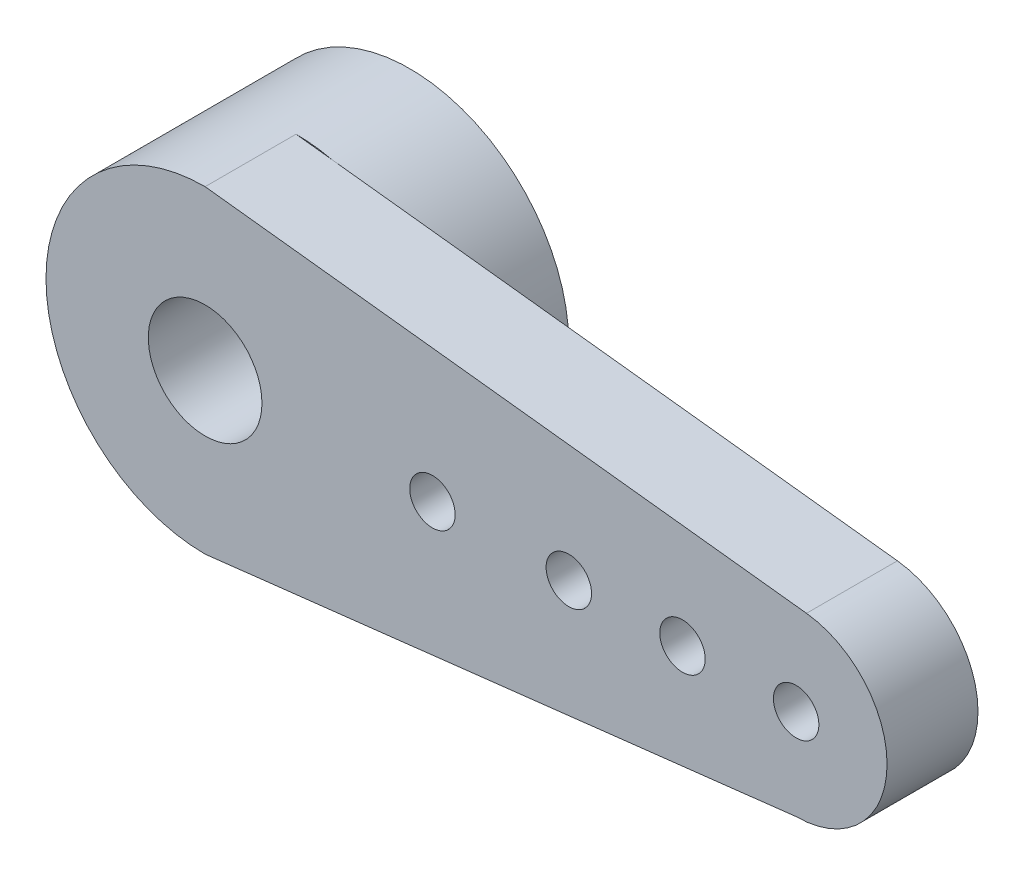
SolidWorks part; units mm, degrees
ref_plane "前基準面" through (0, 0, 0) normal (0, 0, 1) x (1, 0, 0)
ref_plane "上基準面" through (0, 0, 0) normal (0, 1, 0) x (1, 0, 0)
ref_plane "右基準面" through (0, 0, 0) normal (1, 0, 0) x (0, 0, -1)
sketch "草圖1" plane through (0, 0, 0) normal (0, 0, 1) x (1, 0, 0)
  line L0 (0, 3.5) -> (13.2273, 1.987)
  line L1 (0, -3.5) -> (13, -2)
  arc A0 (0, 3.5) -> (0, -3.5) centre (0, 0) ccw
  arc A1 (13, -2) -> (13.2273, 1.987) centre (13, 0) ccw
  circle A2 centre (0, 0) radius 1.25
  circle A3 centre (13, 0) radius 0.5
  dimension "D1" = 7
  dimension "D2" = 4
  dimension "D4" = 2.5
  dimension "D5" = 1
  dimension "D3" = 13
extrude "填料-伸長1" add sketch "草圖1" along normal blind 2
sketch "草圖2" plane through (0, 0, 2) normal (0, 0, 1) x (1, 0, 0)
  circle A1 centre (10.5, 0) radius 0.5
  circle A2 centre (8, 0) radius 0.5
  circle A3 centre (5, 0) radius 0.5
  dimension "D5" = 1
  dimension "D6" = 1
  dimension "D7" = 1
  dimension "D1" = 5
  dimension "D3" = 2.5
  dimension "D4" = 3
extrude "除料-伸長1" cut sketch "草圖2" against normal up to next
sketch "草圖3" plane through (0, 0, 0) normal (0, 0, -1) x (-1, 0, 0)
  circle A0 centre (0, 0) radius 3.5
  circle A1 centre (0, 0) radius 2.5
  dimension "D1" = 7
  dimension "D2" = 5
extrude "填料-伸長2" add sketch "草圖3" along normal blind 2.5
